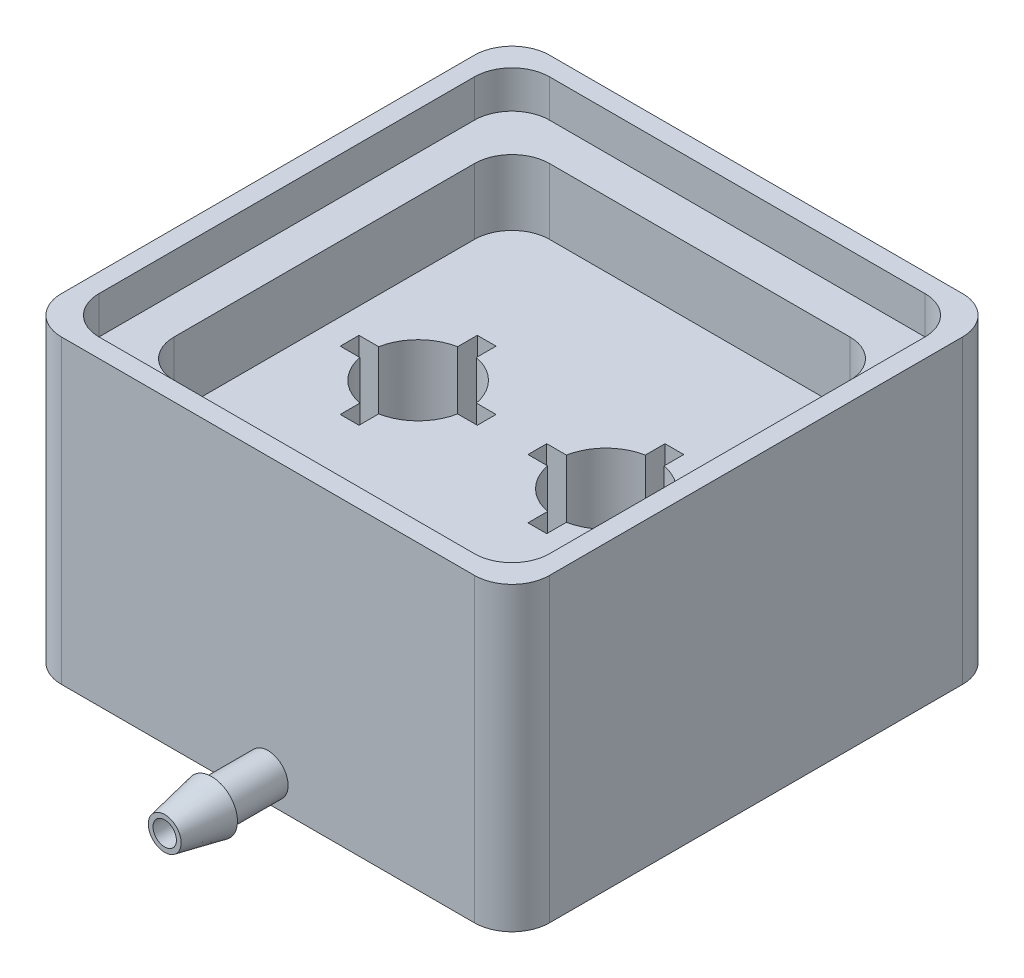
SolidWorks part; units mm, degrees
ref_plane "Front Plane" through (0, 0, 0) normal (0, 0, 1) x (1, 0, 0)
ref_plane "Top Plane" through (0, 0, 0) normal (0, 1, 0) x (1, 0, 0)
ref_plane "Right Plane" through (0, 0, 0) normal (1, 0, 0) x (0, 0, -1)
sketch "Sketch1" plane through (0, 0, 0) normal (0, 1, 0) x (1, 0, 0)
  line L0 (-5, 0) -> (5, 0) construction
  line L1 (-11, -13) -> (11, -13)
  line L2 (-13, -11) -> (-13, 11)
  line L3 (-11, 13) -> (11, 13)
  line L4 (13, -11) -> (13, 11)
  line L5 (-13, -13) -> (13, 13) construction
  line L6 (-13, 13) -> (13, -13) construction
  arc A0 (-13, 11) -> (-11, 13) centre (-11, 11) cw
  arc A1 (11, 13) -> (13, 11) centre (11, 11) cw
  arc A2 (-13, -11) -> (-11, -13) centre (-11, -11) ccw
  arc A3 (13, -11) -> (11, -13) centre (11, -11) cw
  circle A4 centre (5, 0) radius 2.65
  circle A5 centre (-5, 0) radius 2.65
  point P0 (0, 0)
  point P21 (0, 0)
  dimension "D3" = 2
  dimension "D4" = 2
  dimension "D6" = 5.3
  dimension "D7" = 5.3
  dimension "D1" = 26
  dimension "D2" = 26
  dimension "D5" = 10
extrude "Boss-Extrude1" add sketch "Sketch1" along normal blind 10.53
sketch "Sketch2" plane through (0, 10.53, 0) normal (0, 1, 0) x (1, 0, 0)
  line L0 (-5, 0) -> (5, 0) construction
  line L2 (-8.65, -0.5) -> (-1.35, -0.5)
  line L3 (-8.65, -0.5) -> (-8.65, 0.5)
  line L4 (-8.65, 0.5) -> (-1.35, 0.5)
  line L5 (-1.35, -0.5) -> (-1.35, 0.5)
  line L6 (-8.65, -0.5) -> (-1.35, 0.5) construction
  line L7 (-8.65, 0.5) -> (-1.35, -0.5) construction
  line L8 (-5.5, -3.65) -> (-4.5, -3.65)
  line L9 (-5.5, -3.65) -> (-5.5, 3.65)
  line L10 (-5.5, 3.65) -> (-4.5, 3.65)
  line L11 (-4.5, -3.65) -> (-4.5, 3.65)
  line L12 (-5.5, -3.65) -> (-4.5, 3.65) construction
  line L13 (-5.5, 3.65) -> (-4.5, -3.65) construction
  line L14 (4.5, -3.65) -> (5.5, -3.65)
  line L15 (4.5, -3.65) -> (4.5, 3.65)
  line L16 (4.5, 3.65) -> (5.5, 3.65)
  line L17 (5.5, -3.65) -> (5.5, 3.65)
  line L18 (4.5, -3.65) -> (5.5, 3.65) construction
  line L19 (4.5, 3.65) -> (5.5, -3.65) construction
  line L20 (1.35, -0.5) -> (8.65, -0.5)
  line L21 (1.35, -0.5) -> (1.35, 0.5)
  line L22 (1.35, 0.5) -> (8.65, 0.5)
  line L23 (8.65, -0.5) -> (8.65, 0.5)
  line L24 (1.35, -0.5) -> (8.65, 0.5) construction
  line L25 (1.35, 0.5) -> (8.65, -0.5) construction
  point P3 (0, 0)
  circle M15 centre (5, 0) radius 2.65
  circle M16 centre (-5, 0) radius 2.65
  dimension "D1" = 10
  dimension "D2" = 7.3
  dimension "D3" = 7.3
  dimension "D4" = 7.3
  dimension "D5" = 7.3
  dimension "D6" = 1
  dimension "D7" = 1
  dimension "D8" = 1
  dimension "D9" = 1
extrude "Cut-Extrude1" cut sketch "Sketch2" against normal blind 9.785 contours L17 L16 L15 M15 | L20 L23 L22 M15 | L14 L17 L15 M15 | L22 L21 L20 M15 | L2 L5 L4 M16 | L11 L10 L9 M16 | L4 L3 L2 M16 | L8 L11 L9 M16
sketch "Sketch3" plane through (0, 0, 0) normal (1, 0, 0) x (0, 0, -1)
  line L0 (-13, 0.3) -> (-16, 0.3)
  line L1 (-13, 10.53) -> (-13, 0) construction
  line L2 (-16, 0.3) -> (-16, 0)
  line L3 (-16, 0) -> (-18.5, 0.5)
  line L4 (-18.5, 0.5) -> (-18.5, 0.75)
  line L5 (-18.5, 0.75) -> (-13, 0.75)
  line L6 (-13, 0.75) -> (-13, 0.3)
  line L7 (-13, 1.375) -> (-13.6025, 1.375) construction
  line L8 (-11, 0) -> (11, 0) construction
  dimension "D1" = 2.5
  dimension "D2" = 3
  dimension "D3" = 0.875
  dimension "D4" = 1.075
  dimension "D5" = 0.625
  dimension "D6" = 1.375
revolve "Revolve1" add sketch "Sketch3" angle 360 about L7
sketch "Sketch10" plane through (0, 0, 0) normal (1, 0, 0) x (0, 0, -1)
  circle A0 centre (0, 1.375) radius 0.625
extrude "Cut-Extrude3" cut sketch "Sketch10" against normal up to next and the other way up to next
sketch "Sketch5" plane through (0, 0, 13) normal (0, 0, 1) x (1, 0, 0)
  circle A0 centre (0, 1.375) radius 0.625
  dimension "D1" = 1.25
extrude "Cut-Extrude2" cut sketch "Sketch5" against normal up to next
sketch "Sketch6" plane through (0, 10.53, 0) normal (0, 1, 0) x (1, 0, 0)
  line L1 (-11, -13) -> (11, -13)
  line L2 (-13, -11) -> (-13, 11)
  line L3 (-11, 13) -> (11, 13)
  line L4 (13, -11) -> (13, 11)
  line L5 (-13, -13) -> (13, 13) construction
  line L6 (-13, 13) -> (13, -13) construction
  line L7 (-8, -10) -> (8, -10)
  line L8 (-10, -8) -> (-10, 8)
  line L9 (-8, 10) -> (8, 10)
  line L10 (10, -8) -> (10, 8)
  line L11 (-10, -10) -> (10, 10) construction
  line L12 (-10, 10) -> (10, -10) construction
  arc A0 (-13, -11) -> (-11, -13) centre (-11, -11) ccw
  arc A1 (13, -11) -> (11, -13) centre (11, -11) cw
  arc A2 (13, 11) -> (11, 13) centre (11, 11) ccw
  arc A3 (-11, 13) -> (-13, 11) centre (-11, 11) ccw
  arc A4 (-10, -8) -> (-8, -10) centre (-8, -8) ccw
  arc A5 (8, -10) -> (10, -8) centre (8, -8) ccw
  arc A6 (10, 8) -> (8, 10) centre (8, 8) ccw
  arc A7 (-8, 10) -> (-10, 8) centre (-8, 8) ccw
  point P0 (0, 0)
  point P18 (0, 0)
  dimension "D3" = 2
  dimension "D1" = 26
  dimension "D2" = 26
  dimension "D6" = 2
  dimension "D4" = 3
  dimension "D5" = 3
extrude "Boss-Extrude2" add sketch "Sketch6" along normal blind 3.5
sketch "Sketch8" plane through (0, 14.03, 0) normal (0, 1, 0) x (1, 0, 0)
  line L1 (-11, -13) -> (11, -13)
  line L2 (-13, -11) -> (-13, 11)
  line L3 (-11, 13) -> (11, 13)
  line L4 (13, -11) -> (13, 11)
  line L5 (-13, -13) -> (13, 13) construction
  line L6 (-13, 13) -> (13, -13) construction
  line L7 (-10, -12) -> (10, -12)
  line L8 (-12, -10) -> (-12, 10)
  line L9 (-10, 12) -> (10, 12)
  line L10 (12, -10) -> (12, 10)
  line L11 (-12, -12) -> (12, 12) construction
  line L12 (-12, 12) -> (12, -12) construction
  arc A0 (13, 11) -> (11, 13) centre (11, 11) ccw
  arc A1 (13, -11) -> (11, -13) centre (11, -11) cw
  arc A2 (-13, -11) -> (-11, -13) centre (-11, -11) ccw
  arc A3 (-13, 11) -> (-11, 13) centre (-11, 11) cw
  arc A4 (-12, -10) -> (-10, -12) centre (-10, -10) ccw
  arc A5 (10, -12) -> (12, -10) centre (10, -10) ccw
  arc A6 (12, 10) -> (10, 12) centre (10, 10) ccw
  arc A7 (-12, 10) -> (-10, 12) centre (-10, 10) cw
  point P0 (0, 0)
  point P18 (0, 0)
  dimension "D3" = 2
  dimension "D1" = 26
  dimension "D2" = 26
  dimension "D6" = 2
  dimension "D4" = 1
  dimension "D5" = 1
extrude "Boss-Extrude3" add sketch "Sketch8" along normal blind 2
equation "\"D2@Sketch1\"=\"D1@Sketch1\""
equation "\"D7@Sketch1\"=\"D6@Sketch1\""
equation "\"D3@Sketch2\"=\"D2@Sketch2\""
equation "\"D2@Sketch2\"=\"D6@Sketch1\"+2mm"
equation "\"D4@Sketch2\"=\"D2@Sketch2\""
equation "\"D5@Sketch2\"=\"D2@Sketch2\""
equation "\"D7@Sketch2\"=\"D6@Sketch2\""
equation "\"D8@Sketch2\"=\"D6@Sketch2\""
equation "\"D9@Sketch2\"=\"D6@Sketch2\""
equation "\"D1@Sketch6\"=\"D1@Sketch1\""
equation "\"D2@Sketch6\"=\"D1@Sketch1\""
equation "\"D5@Sketch6\"=\"D4@Sketch6\""
equation "\"D1@Sketch8\"=\"D1@Sketch1\""
equation "\"D2@Sketch8\"=\"D1@Sketch1\""
equation "\"D1@Sketch2\"=\"D5@Sketch1\""
